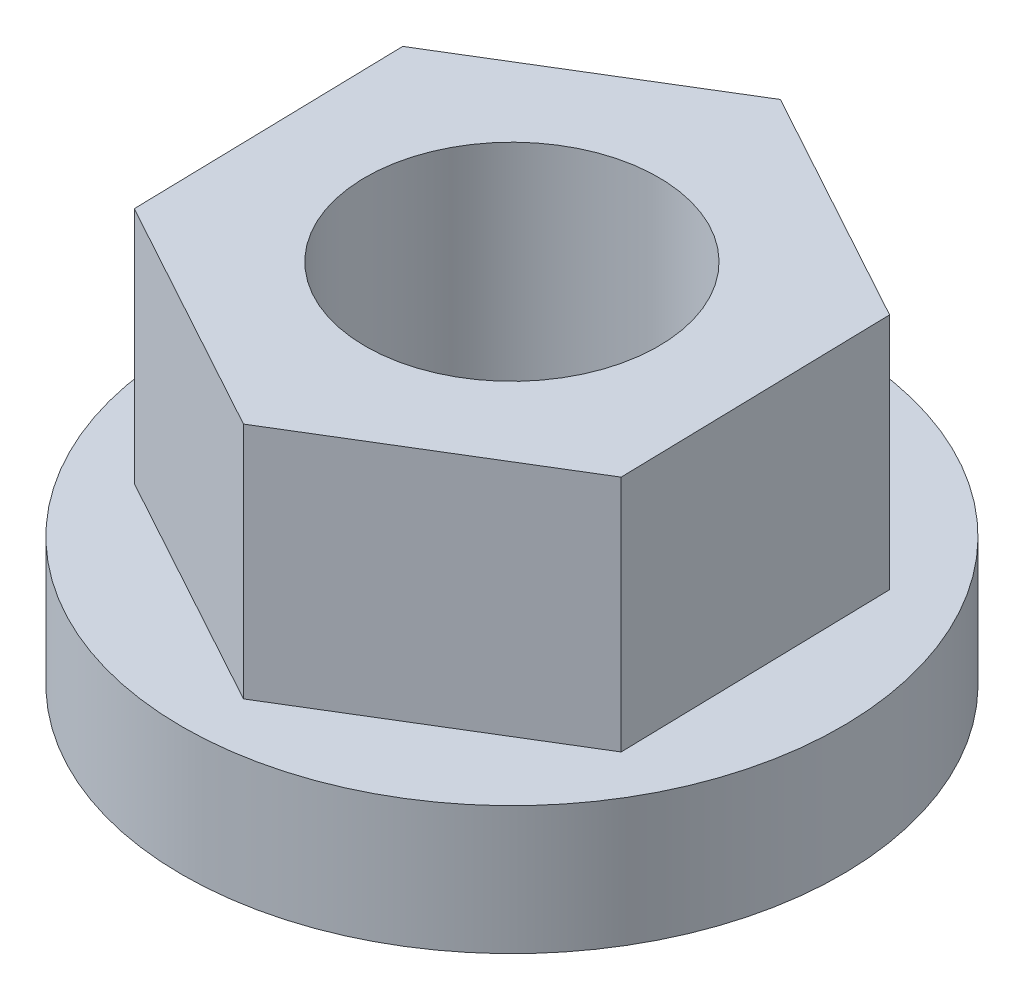
SolidWorks part; units mm, degrees
ref_plane "前视基准面" through (0, 0, 0) normal (0, 0, 1) x (1, 0, 0)
ref_plane "上视基准面" through (0, 0, 0) normal (0, 1, 0) x (1, 0, 0)
ref_plane "右视基准面" through (0, 0, 0) normal (1, 0, 0) x (0, 0, -1)
sketch "草图1" plane through (0, 0, 0) normal (0, 1, 0) x (1, 0, 0)
  circle A0 centre (0, 0) radius 9
  circle A1 centre (0, 0) radius 4
  dimension "D1" = 18
  dimension "D2" = 8
extrude "拉伸1" add sketch "草图1" along normal blind 10
sketch "草图2" plane through (0, 10, 0) normal (0, 1, 0) x (1, 0, 0)
  line L1 (6.5847, -3.6021) -> (6.4118, 3.9015)
  line L2 (6.4118, 3.9015) -> (-0.1729, 7.5036)
  line L3 (-0.1729, 7.5036) -> (-6.5847, 3.6021)
  line L4 (-6.5847, 3.6021) -> (-6.4118, -3.9015)
  line L5 (-6.4118, -3.9015) -> (0.1729, -7.5036)
  line L6 (0.1729, -7.5036) -> (6.5847, -3.6021)
  circle A0 centre (0, 0) radius 6.5 construction
  circle A1 centre (0, 0) radius 9.4991
  dimension "D1" = 13
extrude "拉伸2" cut sketch "草图2" against normal blind 6.5
